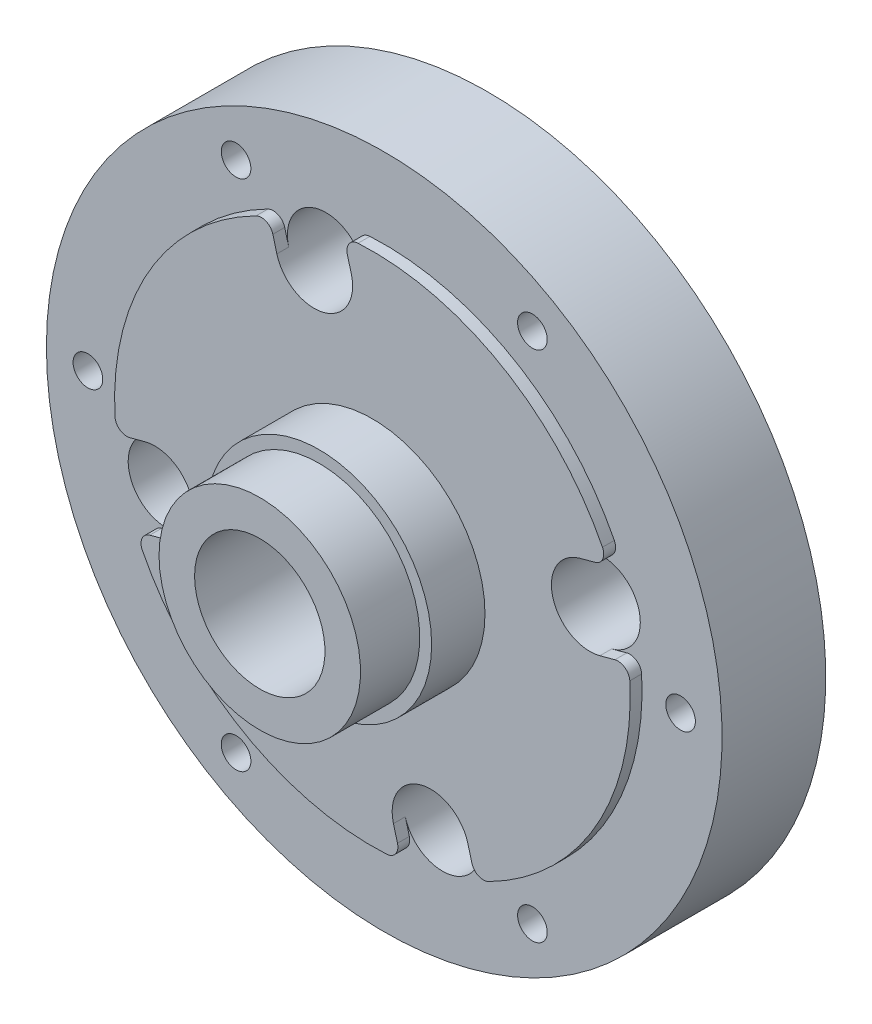
SolidWorks part; units mm, degrees
ref_plane "前视基准面" through (0, 0, 0) normal (0, 0, 1) x (1, 0, 0)
ref_plane "上视基准面" through (0, 0, 0) normal (0, 1, 0) x (1, 0, 0)
ref_plane "右视基准面" through (0, 0, 0) normal (1, 0, 0) x (0, 0, -1)
ref_plane "基准面1" through (0, 0, 0) normal (0, -1, 0) x (1, 0, 0)
sketch "草图1" plane through (0, 0, 0) normal (0, -1, 0) x (1, 0, 0)
  line L0 (28.5, 8.75) -> (0, 8.75)
  line L1 (0, 8.75) -> (0, 0)
  line L2 (0, 0) -> (28.5, 0)
  line L3 (28.5, 0) -> (28.5, 8.75)
  line L4 (0, 8.75) -> (0, 0) construction
revolve "旋转1" add sketch "草图1" angle 360 about L4
sketch "草图2" plane through (0, 0, 8.75) normal (0, 0, 1) x (1, 0, 0)
  line L0 (-8.7054, 19.9319) -> (-8.0568, 17.5114)
  line L1 (-1.7783, 19.1938) -> (-2.4269, 21.6142)
  line L2 (19.9319, 8.7054) -> (17.5114, 8.0568)
  line L3 (19.1938, 1.7783) -> (21.6142, 2.4269)
  line L4 (8.7054, -19.9319) -> (8.0568, -17.5114)
  line L5 (1.7783, -19.1938) -> (2.4269, -21.6142)
  line L6 (-19.9319, -8.7054) -> (-17.5114, -8.0568)
  line L7 (-19.1938, -1.7783) -> (-21.6142, -2.4269)
  arc A0 (-8.0568, 17.5114) -> (-1.7783, 19.1938) centre (-4.9176, 18.3526) cw
  arc A1 (-2.4269, 21.6142) -> (19.9319, 8.7054) centre (0, 0) cw
  arc A2 (17.5114, 8.0568) -> (19.1938, 1.7783) centre (18.3526, 4.9176) cw
  arc A3 (21.6142, 2.4269) -> (8.7054, -19.9319) centre (0, 0) cw
  arc A4 (8.0568, -17.5114) -> (1.7783, -19.1938) centre (4.9176, -18.3526) cw
  arc A5 (2.4269, -21.6142) -> (-19.9319, -8.7054) centre (0, 0) cw
  arc A6 (-17.5114, -8.0568) -> (-19.1938, -1.7783) centre (-18.3526, -4.9176) cw
  arc A7 (-21.6142, -2.4269) -> (-8.7054, 19.9319) centre (0, 0) cw
extrude "凸台-拉伸1" add sketch "草图2" along normal blind 1
sketch "草图3" plane through (0, 0, 0) normal (0, -1, 0) x (1, 0, 0)
  line L0 (8.5, 19.25) -> (0, 19.25)
  line L1 (0, 19.25) -> (0, 9.75)
  line L2 (0, 9.75) -> (9.5, 9.75)
  line L3 (9.5, 9.75) -> (9.5, 14.25)
  line L4 (9.5, 14.25) -> (8.5, 14.25)
  line L5 (8.5, 14.25) -> (8.5, 19.25)
  line L6 (0, 19.25) -> (0, 9.75) construction
revolve "旋转2" add sketch "草图3" angle 360 about L6
ref_plane "基准面2" through (0, -18.3526, 0) normal (0, 1, 0) x (1, 0, 0)
sketch "草图4" plane through (0, -18.3526, 0) normal (0, 1, 0) x (1, 0, 0)
  line L0 (6.6176, 0) -> (4.9176, 0)
  line L1 (4.9176, 0) -> (4.9176, -9.75)
  line L2 (4.9176, -9.75) -> (8.1676, -9.75)
  line L3 (8.1676, -9.75) -> (8.1676, -2.5)
  line L4 (8.1676, -2.5) -> (6.6176, -2.5)
  line L5 (6.6176, -2.5) -> (6.6176, 0)
  line L6 (4.9176, 0) -> (4.9176, -9.75) construction
revolve "切除-旋转1" cut sketch "草图4" angle 360 about L6
ref_plane "基准面3" through (0, -4.9176, 0) normal (0, 1, 0) x (1, 0, 0)
sketch "草图5" plane through (0, -4.9176, 0) normal (0, 1, 0) x (1, 0, 0)
  line L0 (-16.6526, 0) -> (-18.3526, 0)
  line L1 (-18.3526, 0) -> (-18.3526, -9.75)
  line L2 (-18.3526, -9.75) -> (-15.1026, -9.75)
  line L3 (-15.1026, -9.75) -> (-15.1026, -2.5)
  line L4 (-15.1026, -2.5) -> (-16.6526, -2.5)
  line L5 (-16.6526, -2.5) -> (-16.6526, 0)
  line L6 (-18.3526, 0) -> (-18.3526, -9.75) construction
revolve "切除-旋转2" cut sketch "草图5" angle 360 about L6
ref_plane "基准面4" through (0, 18.3526, 0) normal (0, 1, 0) x (1, 0, 0)
sketch "草图6" plane through (0, 18.3526, 0) normal (0, 1, 0) x (1, 0, 0)
  line L0 (-3.2176, 0) -> (-4.9176, 0)
  line L1 (-4.9176, 0) -> (-4.9176, -9.75)
  line L2 (-4.9176, -9.75) -> (-1.6676, -9.75)
  line L3 (-1.6676, -9.75) -> (-1.6676, -2.5)
  line L4 (-1.6676, -2.5) -> (-3.2176, -2.5)
  line L5 (-3.2176, -2.5) -> (-3.2176, 0)
  line L6 (-4.9176, 0) -> (-4.9176, -9.75) construction
revolve "切除-旋转3" cut sketch "草图6" angle 360 about L6
ref_plane "基准面5" through (0, 4.9176, 0) normal (0, 1, 0) x (1, 0, 0)
sketch "草图7" plane through (0, 4.9176, 0) normal (0, 1, 0) x (1, 0, 0)
  line L0 (20.0526, 0) -> (18.3526, 0)
  line L1 (18.3526, 0) -> (18.3526, -9.75)
  line L2 (18.3526, -9.75) -> (21.6026, -9.75)
  line L3 (21.6026, -9.75) -> (21.6026, -2.5)
  line L4 (21.6026, -2.5) -> (20.0526, -2.5)
  line L5 (20.0526, -2.5) -> (20.0526, 0)
  line L6 (18.3526, 0) -> (18.3526, -9.75) construction
revolve "切除-旋转4" cut sketch "草图7" angle 360 about L6
hole_wizard "M10 六角头螺栓的柱形沉头孔1" positions "草图9" profile "草图8" counterbore size "M10" standard "ANSI Metric"
sketch "草图9" plane through (0, 0, 0) normal (0, 0, -1) x (-1, 0, 0)
  point P0 (0, 0)
sketch "草图8" plane through (0, 0, 0) normal (1, 0, 0) x (0, 1, 0)
  line L0 (0, 0) -> (0, 19.25)
  line L1 (0, 19.25) -> (5.5, 19.25)
  line L3 (5.5, 19.25) -> (5.5, 6.75)
  line L4 (5.5, 6.75) -> (14.25, 6.75)
  line L5 (14.25, 6.75) -> (14.25, 0)
  line L7 (14.25, 0) -> (0, 0)
  line L11 (0, -6.35) -> (0, 107.95) construction
  dimension "通孔孔直径" = 11
  dimension "通孔孔深度" = 19.25
  dimension "柱形沉头孔直径" = 28.5
  dimension "柱形沉头孔深度" = 6.75
hole_wizard "Ø2.5 (2.5) 直径孔1" positions "草图11" profile "草图10" hole size "Ø2.5" standard "ANSI Metric"
sketch "草图11" plane through (0, 0, 0) normal (0, 0, -1) x (-1, 0, 0)
  point P0 (-25, 0)
  point P1 (-12.5, 21.6506)
  point P2 (12.5, 21.6506)
  point P3 (25, 0)
  point P4 (12.5, -21.6506)
  point P5 (-12.5, -21.6506)
sketch "草图10" plane through (25, 0, 0) normal (1, 0, 0) x (0, 1, 0)
  line L0 (0, 0) -> (0, 19.25)
  line L1 (0, 19.25) -> (1.25, 19.25)
  line L2 (1.25, 19.25) -> (1.25, 0)
  line L5 (1.25, 0) -> (0, 0)
  line L11 (0, -6.35) -> (0, 107.95) construction
  dimension "通孔孔直径" = 2.5
  dimension "通孔孔深度" = 19.25
fillet "圆角1" radius 1 8 edges at (2.4269, -21.6142, 9.25) (-21.6142, -2.4269, 9.25) (-19.9319, -8.7054, 9.25) (21.6142, 2.4269, 9.25) (19.9319, 8.7054, 9.25) (-8.7054, 19.9319, 9.25) (8.7054, -19.9319, 9.25) (-2.4269, 21.6142, 9.25)
